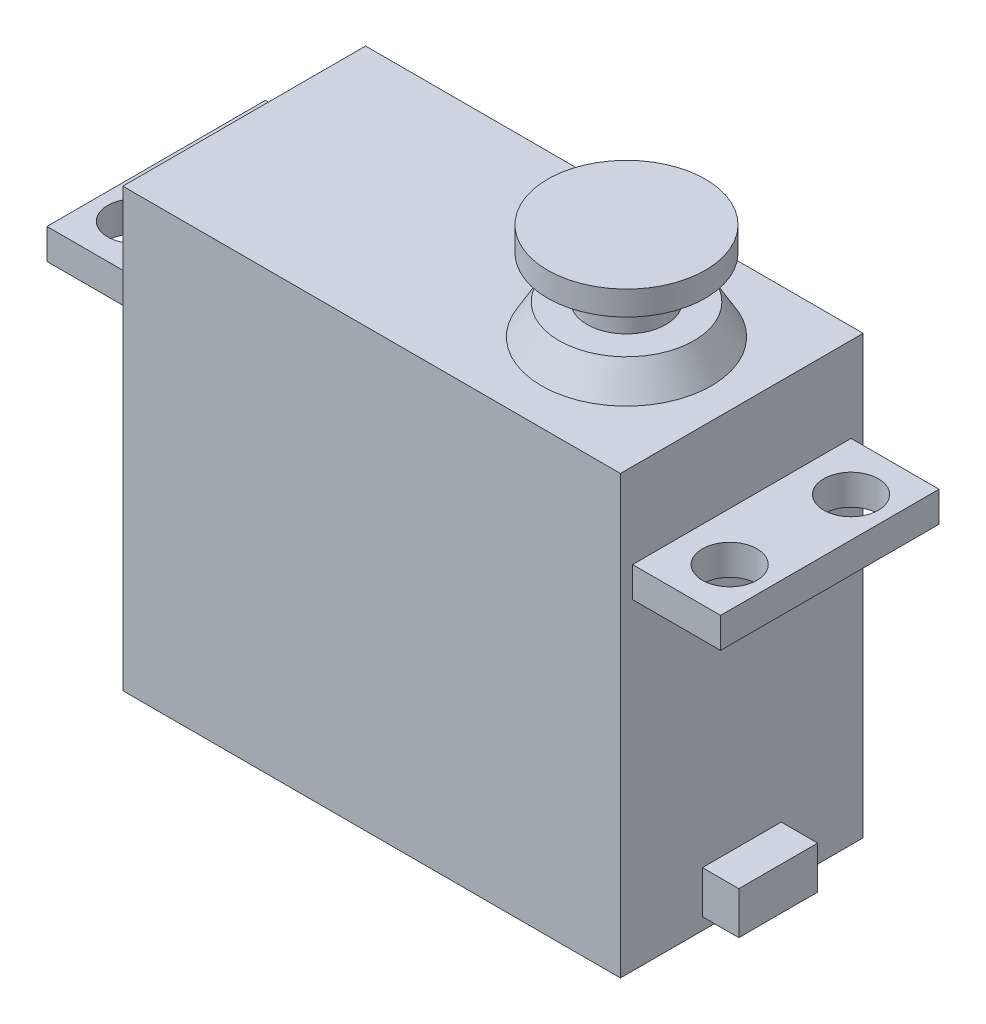
SolidWorks part; units mm, degrees
ref_plane "Front Plane" through (0, 0, 0) normal (0, 0, 1) x (1, 0, 0)
ref_plane "Top Plane" through (0, 0, 0) normal (0, 1, 0) x (1, 0, 0)
ref_plane "Right Plane" through (0, 0, 0) normal (1, 0, 0) x (0, 0, -1)
sketch "Sketch1" plane through (0, 0, 0) normal (0, 1, 0) x (1, 0, 0)
  line L1 (-20.5, -10) -> (20.5, -10)
  line L2 (-20.5, -10) -> (-20.5, 10)
  line L3 (-20.5, 10) -> (20.5, 10)
  line L4 (20.5, -10) -> (20.5, 10)
  line L5 (-20.5, -10) -> (20.5, 10) construction
  line L6 (-20.5, 10) -> (20.5, -10) construction
  point P0 (0, 0)
  dimension "D1" = 20
  dimension "D2" = 41
extrude "Boss-Extrude1" add sketch "Sketch1" along normal blind 36 contours L2 L3 L4 L1
sketch "Sketch2" plane through (0, 0, 0) normal (0, -1, 0) x (1, 0, 0)
  line L1 (-27.75, 9) -> (27.75, 9)
  line L2 (-27.75, 9) -> (-27.75, -9)
  line L3 (-27.75, -9) -> (27.75, -9)
  line L4 (27.75, 9) -> (27.75, -9)
  line L5 (-27.75, 9) -> (27.75, -9) construction
  line L6 (-27.75, -9) -> (27.75, 9) construction
  point P0 (0, 0)
  dimension "D1" = 18
  dimension "D2" = 55.5
extrude "Boss-Extrude2" add sketch "Sketch2" against normal blind 2.5 from offset 26.5 offset against normal yes
sketch "Sketch3" plane through (20.5, 0, 0) normal (1, 0, 0) x (0, 0, -1)
  line L0 (-10, 0) -> (10, 0) construction
  line L1 (-3.25, 1) -> (3.25, 1)
  line L2 (-3.25, 1) -> (-3.25, 4.5)
  line L3 (-3.25, 4.5) -> (3.25, 4.5)
  line L4 (3.25, 1) -> (3.25, 4.5)
  line L5 (-3.25, 1) -> (3.25, 4.5) construction
  line L6 (-3.25, 4.5) -> (3.25, 1) construction
  point P0 (0, 2.75)
  dimension "D1" = 1
  dimension "D2" = 3.5
  dimension "D3" = 6.5
extrude "Boss-Extrude3" add sketch "Sketch3" along normal blind 3
sketch "Sketch4" plane through (0, 36, 0) normal (0, 1, 0) x (1, 0, 0)
  line L1 (20.5, 9) -> (20.5, -9) construction
  circle A0 centre (11, 0) radius 7
  point P6 (18, 0)
  dimension "D1" = 14
  dimension "D2" = 2.5
extrude "Boss-Extrude4" add sketch "Sketch4" along normal blind 2.5 draft 30
sketch "Sketch5" plane through (0, 36, 0) normal (0, 1, 0) x (1, 0, 0)
  circle A0 centre (11, 0) radius 3.25
  dimension "D1" = 6.5
extrude "Boss-Extrude6" add sketch "Sketch5" along normal blind 8
sketch "Sketch6" plane through (0, 44, 0) normal (0, 1, 0) x (1, 0, 0)
  circle A0 centre (11, 0) radius 6.5
  dimension "D1" = 13
extrude "Boss-Extrude7" add sketch "Sketch6" against normal blind 2
sketch "Sketch7" plane through (0, 0, 0) normal (0, 0, 1) x (1, 0, 0)
  line L0 (11, 44) -> (11, -1.8947) construction
  line L1 (17.5, 44) -> (4.5, 44) construction
sketch "Sketch8" plane through (0, 0, 0) normal (0, -1, 0) x (1, 0, 0)
  line L1 (27.75, -9) -> (-27.75, -9)
  line L2 (27.75, 0) -> (11, 0)
  line L3 (27.75, -9) -> (27.75, 9) construction
sketch "Sketch9" plane through (0, 29, 0) normal (0, 1, 0) x (1, 0, 0)
  line L0 (-27.75, 0) -> (27.75, 0) construction
  line L1 (-27.75, -9) -> (-27.75, 9) construction
  line L2 (27.75, 9) -> (27.75, -9) construction
  line L3 (0, 10) -> (0, -10) construction
  line L4 (-20.5, 10) -> (20.5, 10) construction
  line L5 (-20.5, -10) -> (20.5, -10) construction
  circle A0 centre (-24.5, 5) radius 2.25
  circle A1 centre (24.5, 5) radius 2.25
  circle A2 centre (-24.5, -5) radius 2.25
  circle A3 centre (24.5, -5) radius 2.25
  dimension "D3" = 4.5
  dimension "D1" = 10
  dimension "D2" = 49
extrude "Cut-Extrude1" cut sketch "Sketch9" against normal blind 10
